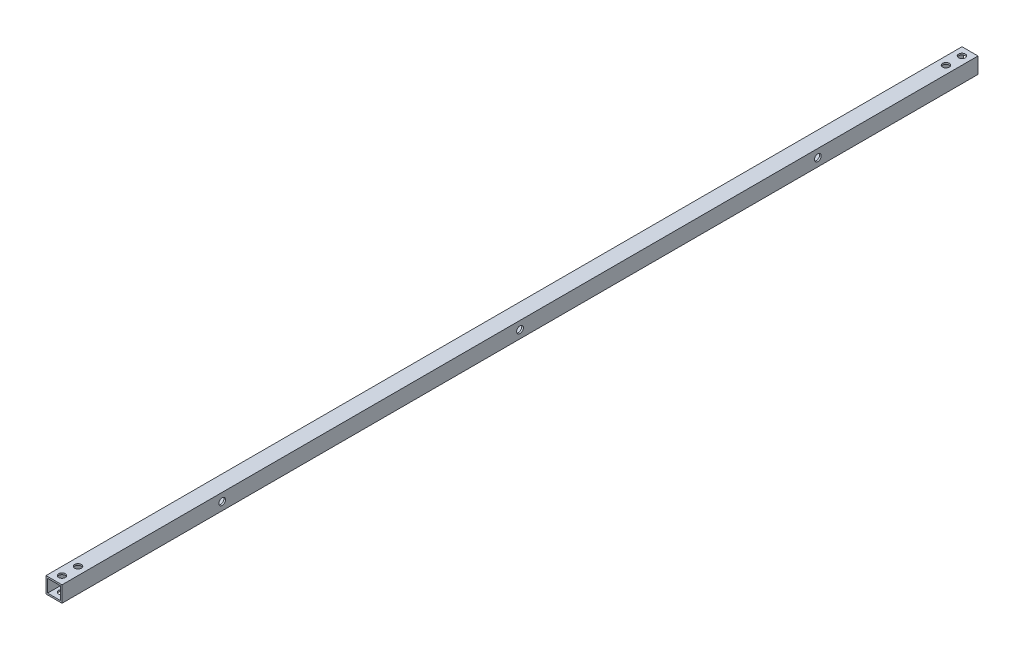
SolidWorks part; units mm, degrees
ref_plane "Front Plane" through (0, 0, 0) normal (0, 0, 1) x (1, 0, 0)
ref_plane "Top Plane" through (0, 0, 0) normal (0, 1, 0) x (1, 0, 0)
ref_plane "Right Plane" through (0, 0, 0) normal (1, 0, 0) x (0, 0, -1)
sketch "Sketch1" plane through (0, 0, 0) normal (0, 0, 1) x (1, 0, 0)
  line L1 (0, 0) -> (10, 0)
  line L2 (0, 0) -> (0, 10)
  line L3 (0, 10) -> (10, 10)
  line L4 (10, 0) -> (10, 10)
  line L5 (1, 9) -> (9, 9)
  line L6 (1, 9) -> (1, 1)
  line L7 (1, 1) -> (9, 1)
  line L8 (9, 9) -> (9, 1)
  dimension "D1" = 10
  dimension "D2" = 10
  dimension "D3" = 8
  dimension "D4" = 8
  dimension "D5" = 1
  dimension "D6" = 1
extrude "Boss-Extrude1" add sketch "Sketch1" along normal blind 572
sketch "Sketch2" plane through (0, 10, 0) normal (0, 1, 0) x (1, 0, 0)
  line L0 (10, 0) -> (0, 0) construction
  line L1 (10, -572) -> (10, 0) construction
  line L2 (0, -572) -> (0, 0) construction
  line L4 (10, -572) -> (0, -572) construction
  circle A0 centre (5, -5) radius 2.1
  circle A1 centre (5, -15) radius 2.1
  circle A2 centre (5, -557) radius 2.1
  circle A3 centre (5, -567) radius 2.1
  dimension "D1" = 4.2
  dimension "D2" = 4.2
  dimension "D7" = 4.2
  dimension "D8" = 4.2
  dimension "D9" = 5
  dimension "D10" = 5
  dimension "D11" = 15
  dimension "D12" = 5
  dimension "D3" = 5
  dimension "D4" = 15
  dimension "D5" = 5
  dimension "D6" = 5
extrude "Cut-Extrude1" cut sketch "Sketch2" against normal blind 116
sketch "Sketch3" plane through (0, 0, 0) normal (0, -1, 0) x (1, 0, 0)
  line L0 (10, 572) -> (10, 0) construction
  line L1 (0, 0) -> (10, 0) construction
  line L2 (0, 572) -> (10, 572) construction
  circle A0 centre (5, 336) radius 2.1
  circle A1 centre (5, 236) radius 2.1
  dimension "D1" = 4.2
  dimension "D2" = 5
  dimension "D3" = 236
  dimension "D4" = 4.2
  dimension "D5" = 5
  dimension "D6" = 236
extrude "Cut-Extrude2" cut sketch "Sketch3" against normal blind 5
sketch "Sketch5" plane through (10, 0, 0) normal (1, 0, 0) x (0, 0, -1)
  line L0 (0, 0) -> (0, 10) construction
  line L1 (-572, 0) -> (-572, 10) construction
  line L2 (-572, 0) -> (0, 0) construction
  circle A0 centre (-472, 5) radius 2.1
  circle A1 centre (-100, 5) radius 2.1
  circle A2 centre (-286, 5) radius 2.1
  dimension "D1" = 4.2
  dimension "D2" = 4.2
  dimension "D3" = 4.2
  dimension "D4" = 100
  dimension "D5" = 100
  dimension "D6" = 286
  dimension "D7" = 5
extrude "Cut-Extrude3" cut sketch "Sketch5" against normal blind 10
